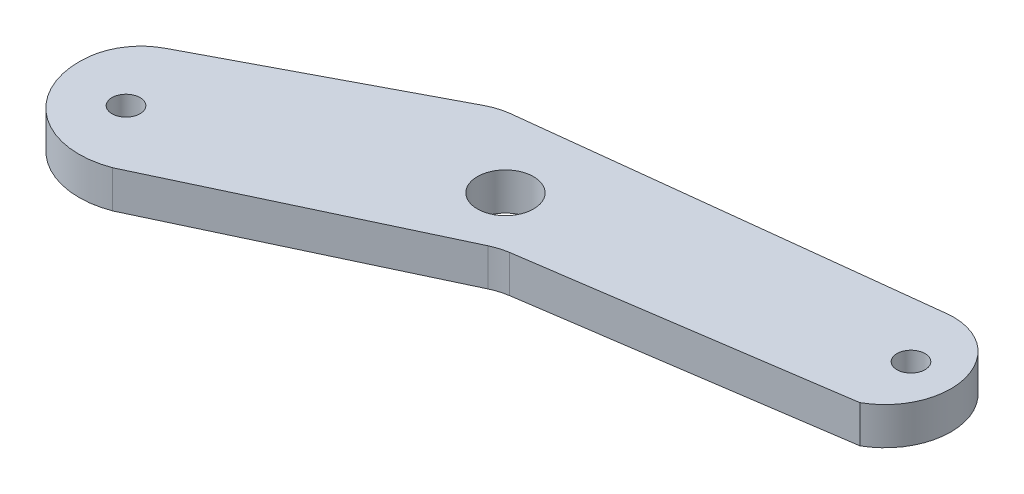
SolidWorks part; units mm, degrees
material "6061-O (SS)"
ref_plane "Alzado" through (0, 0, 0) normal (0, 0, 1) x (1, 0, 0)
ref_plane "Planta" through (0, 0, 0) normal (0, 1, 0) x (1, 0, 0)
ref_plane "Vista lateral" through (0, 0, 0) normal (1, 0, 0) x (0, 0, -1)
sketch "Croquis1" plane through (0, 0, 0) normal (0, 1, 0) x (1, 0, 0)
  line L3 (47.875, 0) -> (47.875, 60.1302) construction
  line L5 (84.2132, 2.3935) -> (80.8557, 23.1233) construction
  line L6 (84.2132, 2.3935) -> (32.4102, -5.2562)
  line L7 (-12.7, -4.7625) -> (-12.7, 38.5825) construction
  line L10 (-21.6937, -80.0806) -> (-21.6937, 3.7748) construction
  line L11 (-13.7071, -26.4826) -> (-29.6803, -5.9678) construction
  line L12 (8.6116, 14.1472) -> (-26.7513, -4.4292)
  line L13 (29.6137, -6.1004) -> (-13.7071, -26.4826)
  line L14 (12.121, 15.229) -> (78.4853, 22.8511)
  circle A0 centre (82.5345, 12.7584) radius 2.3813
  circle A1 centre (23.3063, 3.1655) radius 4.7625
  arc A2 (87.1976, 19.449) -> (84.2132, 2.3935) centre (78.7288, 12.142) cw
  circle A3 centre (-21.6937, -16.2252) radius 2.3812
  arc A4 (-32.0126, -11.9568) -> (-13.7071, -26.4826) centre (-18.5273, -13.7598) ccw
  arc A5 (12.121, 15.229) -> (8.6116, 14.1472) centre (13.2621, 5.2943) ccw
  arc A6 (32.4102, -5.2562) -> (29.6137, -6.1004) centre (33.871, -15.1489) ccw
  arc A7 (-32.0126, -11.9568) -> (-26.7513, -4.4292) centre (-22.1008, -13.282) cw
  arc A8 (78.4853, 22.8511) -> (87.1976, 19.449) centre (79.6263, 12.9164) cw
  point P3 (0, 0)
  point P13 (82.5345, 12.7584)
  point P16 (23.3063, -1.597)
  point P20 (82.5345, 12.7584)
  point P29 (-21.6937, -16.2252)
  dimension "D4" = 4.7625
  dimension "D5" = 9.525
  dimension "D13" = 4.7625
  dimension "D10" = 10
  dimension "D16" = 10
  dimension "D17" = 10
  dimension "D2" = 11.0695
  dimension "D3" = 60
  dimension "D6" = 45
  dimension "D7" = 49
  dimension "D8" = 21
  dimension "D14" = 26
extrude "Saliente-Extruir1" add sketch "Croquis1" along normal blind 6.35
sketch "Croquis2" plane through (0, 6.35, 0) normal (0, 1, 0) x (1, 0, 0)
  line L0 (82.5345, 12.7584) -> (117.8491, 12.7584) construction
  line L1 (80.5027, 22.8779) -> (119.4821, 22.8779) construction
  arc A1 (87.1976, 19.449) -> (78.4853, 22.8511) centre (79.6263, 12.9164) ccw construction
  point P0 (82.5345, 12.7584)
  dimension "D1" = 10.1195
